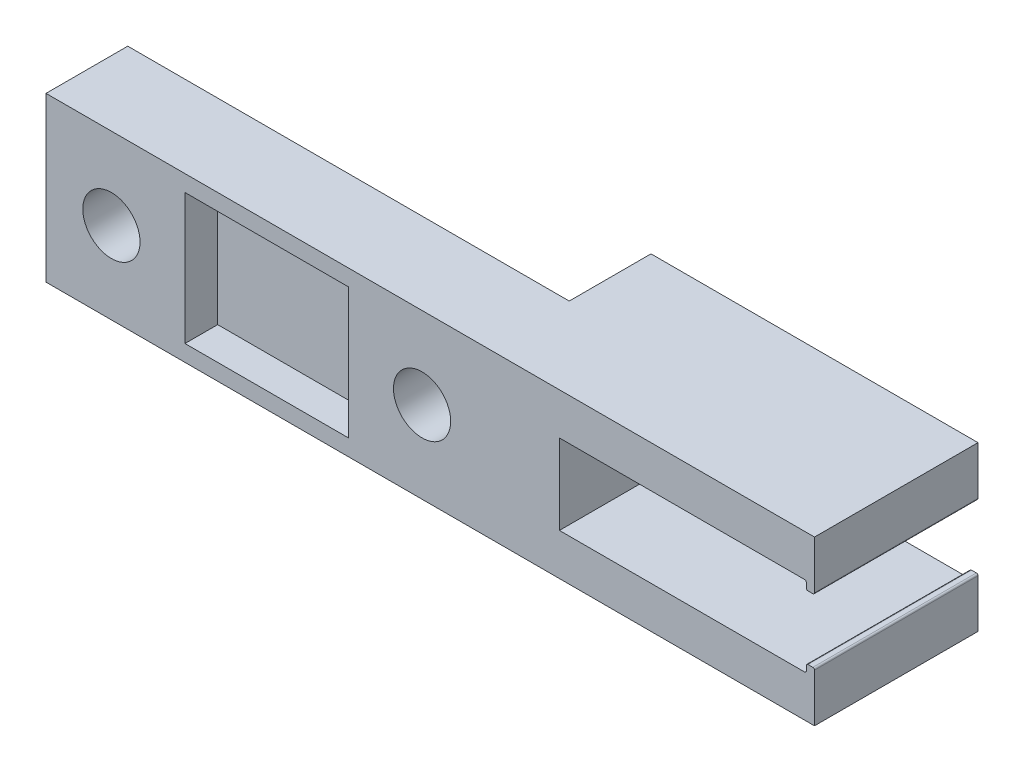
SolidWorks part; units mm, degrees
ref_plane "Front Plane" through (0, 0, 0) normal (0, 0, 1) x (1, 0, 0)
ref_plane "Top Plane" through (0, 0, 0) normal (0, 1, 0) x (1, 0, 0)
ref_plane "Right Plane" through (0, 0, 0) normal (1, 0, 0) x (0, 0, -1)
sketch "Sketch1" plane through (0, 0, 0) normal (0, 0, 1) x (1, 0, 0)
  line L1 (0, 0) -> (20, 0)
  line L2 (0, 0) -> (0, -10)
  line L3 (0, -10) -> (20, -10)
  line L4 (20, 0) -> (20, -10)
  line L5 (4.4, -2.55) -> (20, -2.55)
  line L6 (4.4, -2.55) -> (4.4, -7.45)
  line L7 (4.4, -7.45) -> (20, -7.45)
  line L8 (20, -2.55) -> (20, -7.45)
  line L9 (19.5, -6.95) -> (20, -6.95)
  line L10 (19.5, -6.95) -> (19.5, -7.45)
  line L11 (19.5, -7.45) -> (20, -7.45)
  line L12 (20, -6.95) -> (20, -7.45)
  line L13 (19.5, -3.05) -> (20, -3.05)
  line L14 (19.5, -3.05) -> (19.5, -2.55)
  line L15 (19.5, -2.55) -> (20, -2.55)
  line L16 (20, -3.05) -> (20, -2.55)
  point P9 (20, -5)
  dimension "D1" = 10
  dimension "D2" = 20
  dimension "D3" = 4.9
  dimension "D4" = 15.6
  dimension "D5" = 0.5
extrude "Boss-Extrude1" add sketch "Sketch1" along normal blind 10 contours L7 L6 L5 L4 L1 L2 L3 | L9 L10 L7 L8 | L14 L13 L4 L5
sketch "Sketch2" plane through (0, 0, 10) normal (0, 0, 1) x (1, 0, 0)
  line L0 (-23, -5) -> (-4, -5) construction
  line L9 (0, 0) -> (-27, 0)
  line L10 (0, 0) -> (0, -10)
  line L11 (0, -10) -> (-27, -10)
  line L12 (-27, 0) -> (-27, -10)
  circle A2 centre (-23, -5) radius 1.75
  circle A3 centre (-4, -5) radius 1.75
  point P10 (-27, -5)
  point P11 (-13.5, -5)
  point P12 (-13.5, 0)
  dimension "D2" = 3.5
  dimension "D1" = 27
  dimension "D3" = 19
extrude "Boss-Extrude2" add sketch "Sketch2" against normal blind 5
sketch "Sketch3" plane through (0, 0, 10) normal (0, 0, 1) x (1, 0, 0)
  line L7 (-23, -5) -> (-4, -5) construction
  line L9 (-18.5, -1) -> (-8.5, -1)
  line L10 (-18.5, -1) -> (-18.5, -9)
  line L11 (-18.5, -9) -> (-8.5, -9)
  line L12 (-8.5, -1) -> (-8.5, -9)
  line L13 (-18.5, -1) -> (-8.5, -9) construction
  line L14 (-18.5, -9) -> (-8.5, -1) construction
  point P2 (-13.5, -5)
  dimension "D1" = 10
  dimension "D2" = 8
extrude "Cut-Extrude3" cut sketch "Sketch3" against normal blind 2
fillet "Fillet1" radius 0.1 2 edges at (19.5, -2.55, 5) (19.5, -7.45, 5)
fillet "Fillet2" radius 0.1 4 edges at (20, -6.95, 5) (19.5, -6.95, 5) (20, -3.05, 5) (19.5, -3.05, 5)
